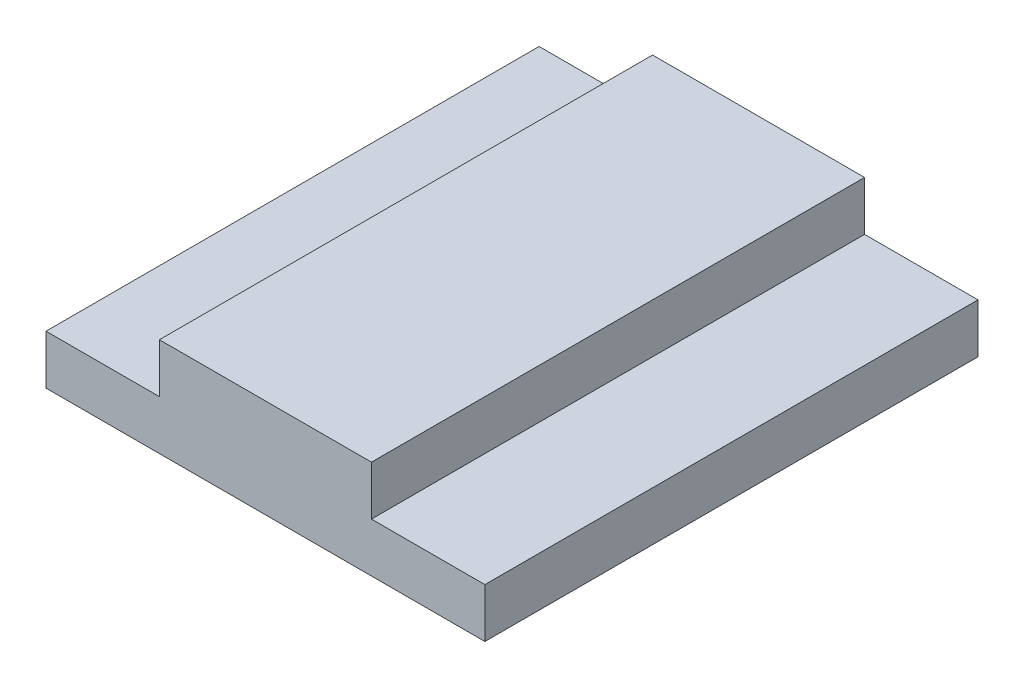
SolidWorks part; units mm, degrees
material "ABS"
ref_plane "Спереди" through (0, 0, 0) normal (0, 0, 1) x (1, 0, 0)
ref_plane "Сверху" through (0, 0, 0) normal (0, 1, 0) x (1, 0, 0)
ref_plane "Справа" through (0, 0, 0) normal (1, 0, 0) x (0, 0, -1)
sketch "Эскиз1" plane through (0, 0, 0) normal (0, 1, 0) x (1, 0, 0)
  line L1 (-44.5, -50) -> (44.5, -50)
  line L2 (-44.5, -50) -> (-44.5, 50)
  line L3 (-44.5, 50) -> (44.5, 50)
  line L4 (44.5, -50) -> (44.5, 50)
  line L5 (-44.5, -50) -> (44.5, 50) construction
  line L6 (-44.5, 50) -> (44.5, -50) construction
  point P0 (0, 0)
  dimension "D1" = 89
  dimension "D2" = 100
extrude "Бобышка-Вытянуть1" add sketch "Эскиз1" along normal blind 10
sketch "Эскиз2" plane through (0, 10, 0) normal (0, 1, 0) x (1, 0, 0)
  line L0 (0, 50) -> (21.5, 50)
  line L1 (44.5, 50) -> (-44.5, 50) construction
  line L2 (21.5, 50) -> (21.5, -50)
  line L3 (-44.5, -50) -> (44.5, -50) construction
  line L4 (21.5, -50) -> (-21.5, -50)
  line L5 (-21.5, -50) -> (-21.5, 50)
  line L6 (-21.5, 50) -> (0, 50)
  dimension "D1" = 43
  dimension "D2" = 21.5
extrude "Бобышка-Вытянуть2" add sketch "Эскиз2" along normal blind 10
